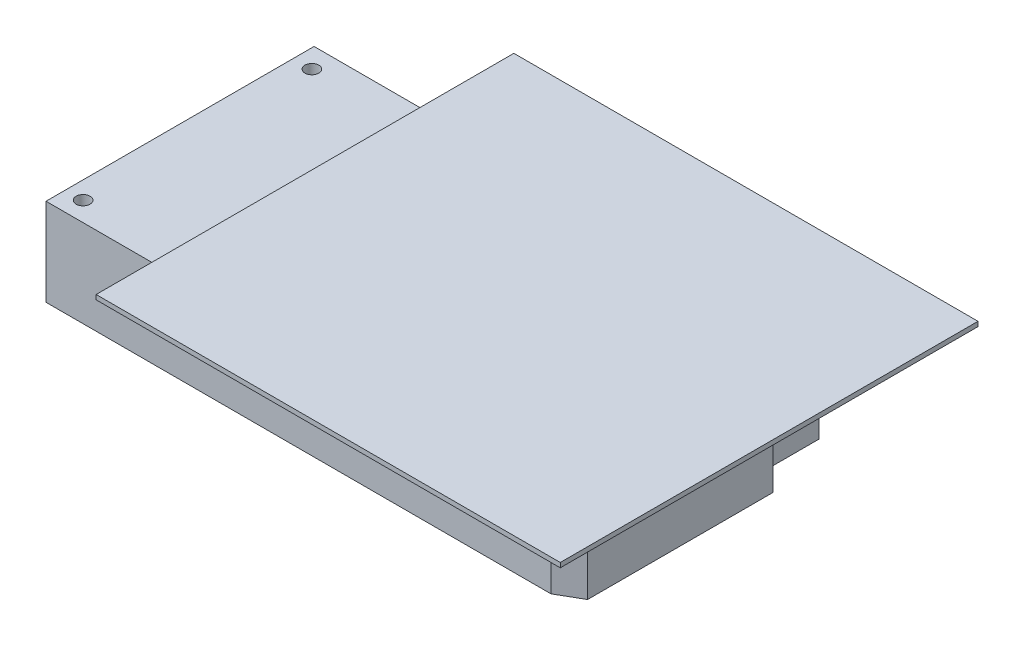
SolidWorks part; units mm, degrees
ref_plane "Front Plane" through (0, 0, 0) normal (0, 0, 1) x (1, 0, 0)
ref_plane "Top Plane" through (0, 0, 0) normal (0, 1, 0) x (1, 0, 0)
ref_plane "Right Plane" through (0, 0, 0) normal (1, 0, 0) x (0, 0, -1)
sketch "Sketch1" plane through (0, 0, 0) normal (0, 1, 0) x (1, 0, 0)
  line L0 (0, 0) -> (0, -57.76)
  line L1 (0, -57.76) -> (108.8, -57.76)
  line L2 (108.8, -57.76) -> (113.8, -54.88)
  line L3 (113.8, -54.88) -> (113.8, -14.88)
  line L4 (113.8, -14.88) -> (108.8, -12)
  line L5 (108.8, -12) -> (108.8, 0)
  line L6 (108.8, 0) -> (0, 0)
  circle A0 centre (66.5, -9.5) radius 1.5
  circle A1 centre (4, -4.47) radius 1.5
  circle A2 centre (3.8, -53.57) radius 1.5
  circle A3 centre (66.5, -48.26) radius 1.5
  dimension "D6" = 3
  dimension "D10" = 4.19
  dimension "D1" = 57.76
  dimension "D2" = 113.8
  dimension "D3" = 5
  dimension "D4" = 40
  dimension "D5" = 12
  dimension "D7" = 4.47
  dimension "D8" = 4
  dimension "D9" = 3.8
  dimension "D11" = 9.5
  dimension "D12" = 9.5
  dimension "D13" = 66.5
extrude "Boss-Extrude1" add sketch "Sketch1" along normal blind 18.86
sketch "Sketch2" plane through (0, 18.86, 0) normal (0, 1, 0) x (1, 0, 0)
  line L1 (23.8, 19.24) -> (123.8, 19.24)
  line L2 (23.8, 19.24) -> (23.8, -70.76)
  line L3 (23.8, -70.76) -> (123.8, -70.76)
  line L4 (123.8, 19.24) -> (123.8, -70.76)
  line L6 (113.8, -54.88) -> (113.8, -14.88) construction
  line L7 (0, -57.76) -> (108.8, -57.76) construction
  dimension "D1" = 90
  dimension "D2" = 10
  dimension "D3" = 13
  dimension "D4" = 100
extrude "Boss-Extrude2" add sketch "Sketch2" along normal blind 1
